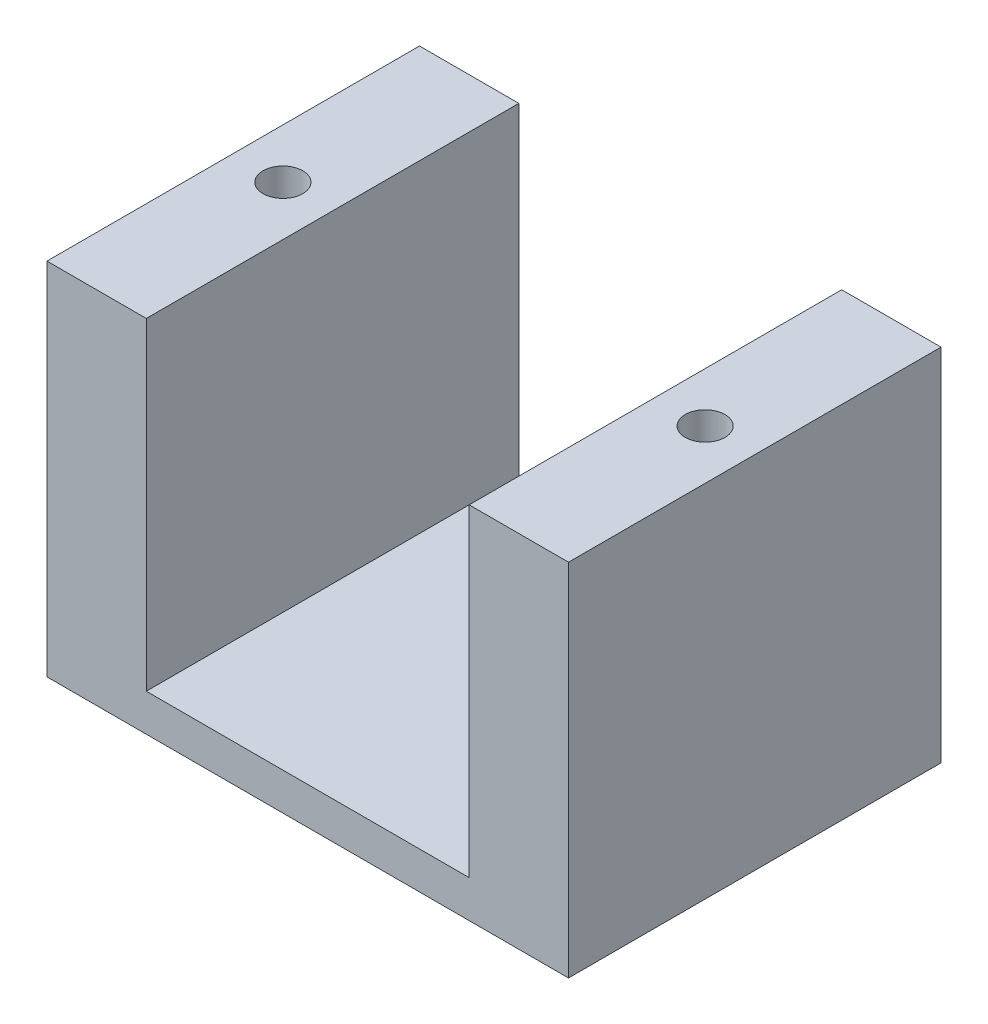
SolidWorks part; units mm, degrees
ref_plane "Alzado" through (0, 0, 0) normal (0, 0, 1) x (1, 0, 0)
ref_plane "Planta" through (0, 0, 0) normal (0, 1, 0) x (1, 0, 0)
ref_plane "Vista lateral" through (0, 0, 0) normal (1, 0, 0) x (0, 0, -1)
sketch "Croquis1" plane through (0, 0, 0) normal (0, 0, 1) x (1, 0, 0)
  line L0 (-21, 0) -> (-21, 29)
  line L1 (-21, 0) -> (21, 0)
  line L3 (-13, 3) -> (13, 3)
  line L5 (-21, 29) -> (-13, 29)
  line L6 (-13, 29) -> (-13, 3)
  line L7 (21, 0) -> (21, 29)
  line L8 (21, 29) -> (13, 29)
  line L9 (13, 29) -> (13, 3)
  point P4 (0, 0)
  dimension "D1" = 3
  dimension "D2" = 42
  dimension "D3" = 8
  dimension "D4" = 8
  dimension "D5" = 29
extrude "Saliente-Extruir1" add sketch "Croquis1" along normal blind 30
sketch "Croquis2" plane through (0, 0, 0) normal (0, -1, 0) x (1, 0, 0)
  line L0 (-21, 30) -> (-21, 0) construction
  line L1 (-21, 30) -> (21, 30) construction
  line L2 (-13, 30) -> (-13, 0) construction
  line L3 (0, 0) -> (0, 30) construction
  line L4 (-21, 0) -> (21, 0) construction
  line L5 (-21, 15) -> (-13, 15) construction
  circle A0 centre (-17, 15) radius 1.6
  circle A1 centre (17, 15) radius 1.6
  point P8 (0, 0)
  point P17 (-17, 15)
  dimension "D2" = 3.2
  dimension "D1" = 8
extrude "Cortar-Extruir1" cut sketch "Croquis2" against normal blind 41 and the other way blind 15
sketch "Croquis3" plane through (0, 0, 0) normal (0, -1, 0) x (1, 0, 0)
  line L0 (0, 0) -> (0, 30) construction
  line L1 (-21, 30) -> (21, 30) construction
  circle A0 centre (-17, 15) radius 2.9
  circle A1 centre (17, 15) radius 2.9
  dimension "D1" = 5.8
extrude "Cortar-Extruir2" cut sketch "Croquis3" against normal blind 3.2
